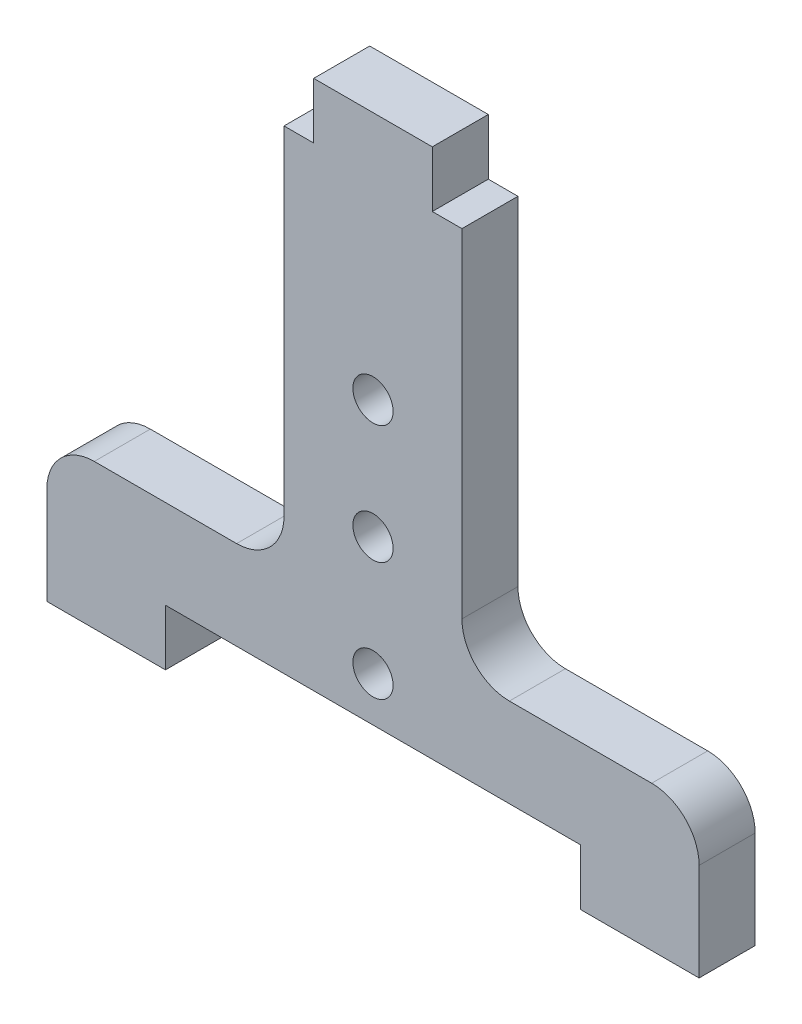
SolidWorks part; units mm, degrees
material "Custom Plastic"
ref_plane "Front Plane" through (0, 0, 0) normal (0, 0, 1) x (1, 0, 0)
ref_plane "Top Plane" through (0, 0, 0) normal (0, 1, 0) x (1, 0, 0)
ref_plane "Right Plane" through (0, 0, 0) normal (1, 0, 0) x (0, 0, -1)
sketch "Sketch1" plane through (0, 0, 0) normal (0, 0, 1) x (1, 0, 0)
  line L1 (-34.925, -25.4) -> (34.925, -25.4)
  line L2 (-34.925, -25.4) -> (-34.925, 25.4)
  line L3 (-34.925, 25.4) -> (34.925, 25.4)
  line L4 (34.925, -25.4) -> (34.925, 25.4)
  line L5 (-34.925, -25.4) -> (34.925, 25.4) construction
  line L6 (-34.925, 25.4) -> (34.925, -25.4) construction
  point P0 (0, 0)
  dimension "D1" = 69.85
  dimension "D2" = 50.8
extrude "Base" add sketch "Sketch1" along normal blind 6
sketch "Sketch6" plane through (0, 0, 6) normal (0, 0, 1) x (1, 0, 0)
  line L0 (34.925, 25.4) -> (-34.925, 25.4) construction
  line L1 (-6.35, 25.4) -> (6.35, 25.4)
  line L2 (-6.35, 25.4) -> (-6.35, 31.4)
  line L3 (-6.35, 31.4) -> (6.35, 31.4)
  line L4 (6.35, 25.4) -> (6.35, 31.4)
  line L5 (0, -25.4) -> (0, 25.4) construction
  line L6 (-34.925, -25.4) -> (34.925, -25.4) construction
  line L7 (22.225, -25.4) -> (22.225, -31.4)
  line L8 (-34.925, -25.4) -> (-22.225, -25.4)
  line L9 (-34.925, -25.4) -> (-34.925, -31.4)
  line L10 (-34.925, -31.4) -> (-22.225, -31.4)
  line L11 (-22.225, -25.4) -> (-22.225, -31.4)
  line L12 (34.925, -31.4) -> (22.225, -31.4)
  line L13 (34.925, -25.4) -> (34.925, -31.4)
  line L14 (34.925, -25.4) -> (22.225, -25.4)
  point P7 (0, 25.4)
  dimension "D1" = 12.7
  dimension "D2" = 6
  dimension "D3" = 6
  dimension "D4" = 12.7
extrude "Boss-Extrude1" add sketch "Sketch6" against normal blind 6
sketch "Sketch7" plane through (0, 0, 6) normal (0, 0, 1) x (1, 0, 0)
  line L1 (-6.35, 25.4) -> (-34.925, 25.4) construction
  line L2 (-9.525, 25.4) -> (-9.525, -15.875)
  line L4 (-9.525, -15.875) -> (-34.925, -15.875)
  line L5 (-34.925, 25.4) -> (-34.925, -31.4) construction
  line L6 (-22.225, -25.4) -> (22.225, -25.4) construction
  line L7 (0, -25.4) -> (0, 31.4) construction
  line L8 (6.35, 31.4) -> (-6.35, 31.4) construction
  line L9 (-9.525, 25.4) -> (-34.925, 25.4)
  line L10 (-34.925, 25.4) -> (-34.925, -15.875)
  dimension "D1" = 9.525
  dimension "D2" = 9.525
extrude "Cut-Extrude1" cut sketch "Sketch7" against normal through all
sketch "Motor mounting sketch" plane through (0, 0, 6) normal (0, 0, 1) x (1, 0, 0)
  line L0 (-34.925, -20.6375) -> (34.925, -20.6375) construction
  line L1 (34.925, -31.4) -> (34.925, 25.4) construction
  line L2 (-34.925, -15.875) -> (-34.925, -31.4) construction
  line L3 (0, 30.121) -> (0, -20.6375) construction
  line L7 (-22.225, -25.4) -> (22.225, -25.4) construction
  point P12 (0, -20.6375)
  point P15 (0, 17.4625)
  point P20 (0, -7.9375)
  point P21 (0, 4.7625)
  dimension "D1" = 4.7625
  dimension "D2" = 12.7
  dimension "D3" = 12.7
  dimension "D4" = 90
  dimension "D5" = 12.7
hole_wizard "#8 Clearance Hole1" positions "Sketch5" profile "Sketch4" hole size "#8" standard "ANSI Inch" end condition through all
sketch "Sketch5" plane through (0, 0, 0) normal (0, 0, -1) x (-1, 0, 0)
  point P3 (0, -20.6375)
  point P31 (0, -7.9375)
  point P34 (0, 4.7625)
sketch "Sketch4" plane through (0, -20.6375, 0) normal (1, 0, 0) x (0, 1, 0)
  line L0 (0, 0) -> (0, 6)
  line L1 (0, 6) -> (2.1526, 6)
  line L2 (2.1526, 6) -> (2.1526, 0)
  line L5 (2.1526, 0) -> (0, 0)
  line L11 (0, -6.35) -> (0, 107.95) construction
  dimension "Thru Hole Dia." = 4.3053
  dimension "Thru Hole Depth" = 6
sketch "Sketch8" plane through (0, 0, 6) normal (0, 0, 1) x (1, 0, 0)
  line L0 (9.525, 25.4) -> (9.525, -15.875)
  line L1 (34.925, 25.4) -> (6.35, 25.4) construction
  line L2 (6.35, 25.4) -> (6.35, 31.4) construction
  line L4 (9.525, -15.875) -> (34.925, -15.875)
  line L5 (34.925, -31.4) -> (34.925, 25.4) construction
  line L6 (34.925, -15.875) -> (34.925, 25.4)
  line L7 (34.925, 25.4) -> (9.525, 25.4)
  line L9 (-34.925, -15.875) -> (-9.525, -15.875) construction
  point P1 (6.35, 28.4)
  dimension "D1" = 3.175
extrude "Cut-Extrude2" cut sketch "Sketch8" against normal through all
fillet "Fillet1" radius 5.08 4 edges at (9.525, -15.875, 3) (34.925, -15.875, 3) (-34.925, -15.875, 3) (-9.525, -15.875, 3)
equation "\"MAT_THICKNESS\"=0.23622"
equation "\"D1@Base\"=\"MAT_THICKNESS\""
equation "\"D2@Sketch6\" = \"MAT_THICKNESS\""
equation "\"D3@Sketch6\"=\"MAT_THICKNESS\""
equation "\"D1@Boss-Extrude1\"=\"MAT_THICKNESS\""
